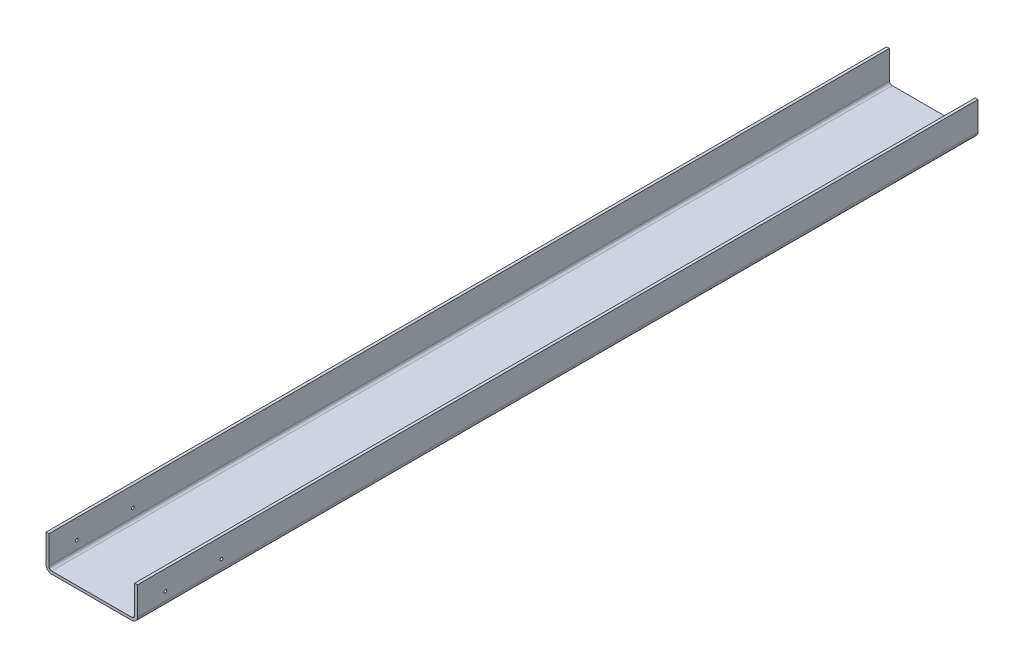
SolidWorks part; units mm, degrees
material "AISI 304"
ref_plane "Спереди" through (0, 0, 0) normal (0, 0, 1) x (1, 0, 0)
ref_plane "Сверху" through (0, 0, 0) normal (0, 1, 0) x (1, 0, 0)
ref_plane "Справа" through (0, 0, 0) normal (1, 0, 0) x (0, 0, -1)
sketch "Эскиз1" plane through (0, 0, 0) normal (0, 0, 1) x (1, 0, 0)
  line L0 (71.5, 0) -> (-71.5, 0)
  line L1 (-81.5, 10) -> (-81.5, 60)
  line L2 (0, -33) -> (0, 33) construction
  line L3 (81.5, 10) -> (81.5, 60)
  line L4 (76.5, 10) -> (76.5, 60)
  line L5 (71.5, 5) -> (-71.5, 5)
  line L6 (-76.5, 10) -> (-76.5, 60)
  line L7 (-81.5, 60) -> (-76.5, 60)
  line L8 (76.5, 60) -> (81.5, 60)
  line L9 (81.5, 0) -> (81.5, 60) construction
  line L10 (81.5, 0) -> (-81.5, 0) construction
  line L11 (-81.5, 0) -> (-81.5, 60) construction
  line L12 (76.5, 5) -> (76.5, 60) construction
  line L13 (76.5, 5) -> (-76.5, 5) construction
  line L14 (-76.5, 5) -> (-76.5, 60) construction
  arc A0 (81.5, 10) -> (71.5, 0) centre (71.5, 10) cw
  arc A1 (-71.5, 0) -> (-81.5, 10) centre (-71.5, 10) cw
  arc A2 (76.5, 10) -> (71.5, 5) centre (71.5, 10) cw
  arc A3 (-71.5, 5) -> (-76.5, 10) centre (-71.5, 10) cw
  point P7 (0, 0)
  point P15 (81.5, 0)
  dimension "D4" = 10
  dimension "D2" = 5
  dimension "D3" = 163
  dimension "D5" = 60
  dimension "D1" = 5
extrude "Бобышка-Вытянуть1" add sketch "Эскиз1" along normal mid plane 1500
sketch "Эскиз2" plane through (81.5, 0, 0) normal (1, 0, 0) x (0, 0, -1)
  line L0 (-750, 10) -> (-750, 60) construction
  line L1 (-750, 0) -> (750, 0) construction
  line L2 (-700, 24.9115) -> (-600, 24.9115) construction
  circle A0 centre (-600, 24.9115) radius 2
  circle A1 centre (-700, 24.9115) radius 2
  dimension "D1" = 4
  dimension "D2" = 50
  dimension "D4" = 24.9115
  dimension "D3" = 100
extrude "Вырез-Вытянуть1" cut sketch "Эскиз2" against normal through all both and the other way through all
hole_wizard "Отверстие обработанное метчиком M61" positions "Эскиз3" profile "Эскиз4" tap size "M6" standard "DIN" end condition through all
sketch "Эскиз3" plane through (81.5, 0, 0) normal (1, 0, 0) x (0, 0, -1)
  point P0 (-600, 24.9115)
  point P3 (-700, 24.9115)
sketch "Эскиз4" plane through (81.5, 24.9115, 600) normal (0, 1, 0) x (0, 0, -1)
  line L0 (0, 0) -> (0, 163)
  line L1 (0, 163) -> (2.5, 163)
  line L2 (2.5, 163) -> (2.5, 0)
  line L5 (2.5, 0) -> (0, 0)
  line L11 (0, -6.35) -> (0, 107.95) construction
  dimension "Диаметр проходного сверла" = 5
  dimension "Глубина проходного сверла" = 163
cosmetic thread "Отверстие резьбы1" parameters "D1"=20, "D2"=6
cosmetic thread "Отверстие резьбы2" parameters "D1"=20, "D2"=6
move or copy body "Тело-Переместить/Копировать3" [suppressed] bodies to move or copy 110 parameters "D1"=0, "D2"=0, "D3"=0
move or copy body "Тело-Переместить/Копировать1" [suppressed] bodies to move or copy 110 parameters "D1"=0, "D2"=0, "D3"=0
move or copy body "Тело-Переместить/Копировать2" [suppressed] bodies to move or copy 108 parameters "D1"=0, "D2"=0, "D3"=0
